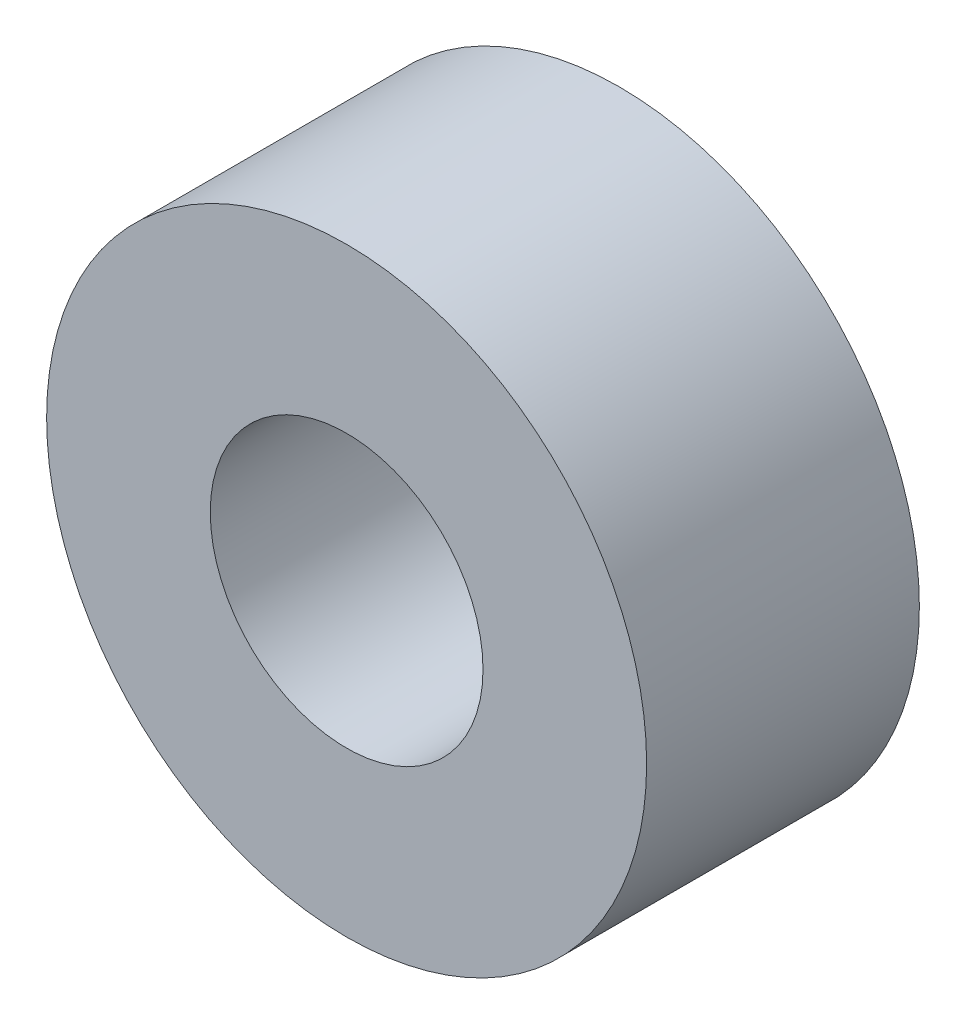
SolidWorks part; units mm, degrees
ref_plane "Front" through (0, 0, 0) normal (0, 0, 1) x (1, 0, 0)
ref_plane "Top" through (0, 0, 0) normal (0, 1, 0) x (1, 0, 0)
ref_plane "Right" through (0, 0, 0) normal (1, 0, 0) x (0, 0, -1)
sketch "Skizze1" plane through (0, 0, 0) normal (0, 0, 1) x (1, 0, 0)
  circle A0 centre (0, 0) radius 5.5
  circle A1 centre (0, 0) radius 2.5
  dimension "D1" = 5
  dimension "D2" = 11
extrude "Aufsatz-Linear austragen1" add sketch "Skizze1" along normal blind 5
